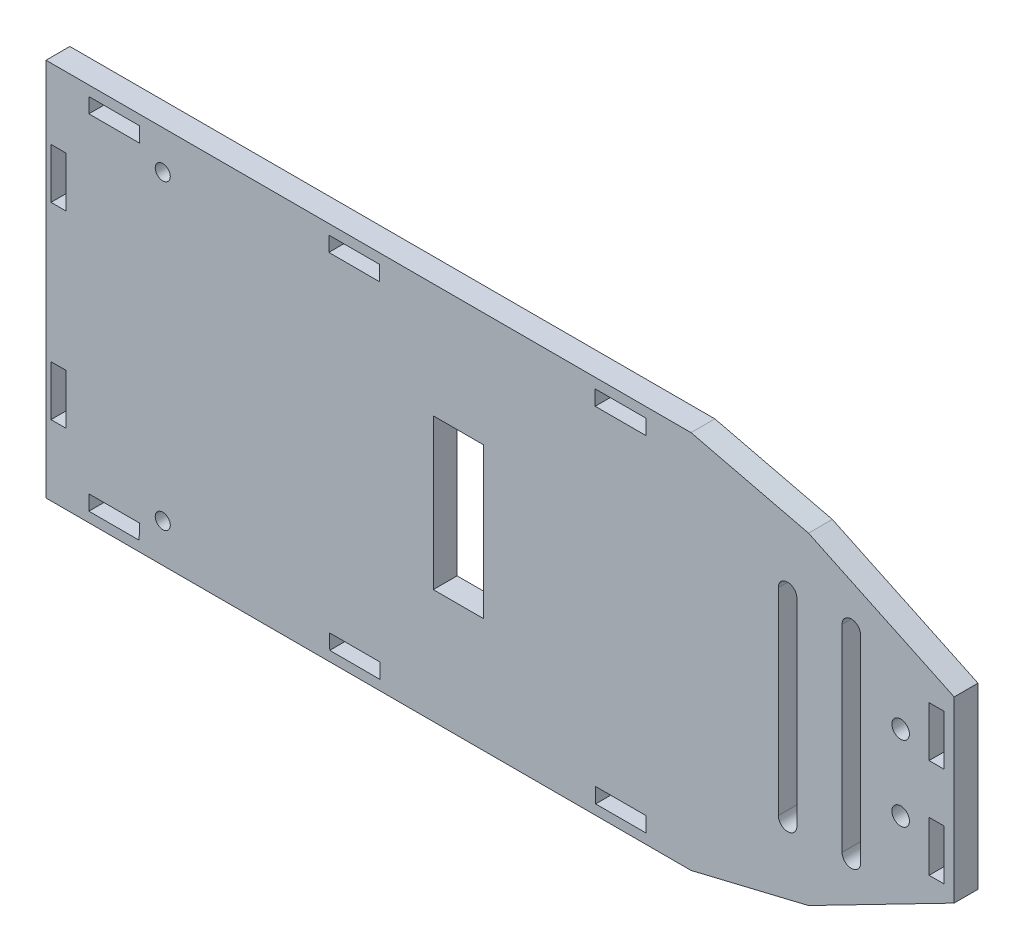
SolidWorks part; units mm, degrees
ref_plane "Front Plane" through (0, 0, 0) normal (0, 0, 1) x (1, 0, 0)
ref_plane "Top Plane" through (0, 0, 0) normal (0, 1, 0) x (1, 0, 0)
ref_plane "Right Plane" through (0, 0, 0) normal (1, 0, 0) x (0, 0, -1)
sketch "Sketch1" plane through (0, 0, 0) normal (0, 0, 1) x (1, 0, 0)
  line L1 (-90.5, -37.785) -> (90.5, -37.785)
  line L2 (-90.5, -37.785) -> (-90.5, 37.785)
  line L3 (-90.5, 37.785) -> (90.5, 37.785)
  line L4 (90.5, -37.785) -> (90.5, 37.785)
  line L5 (-90.5, -37.785) -> (90.5, 37.785) construction
  line L6 (-90.5, 37.785) -> (90.5, -37.785) construction
  point P0 (0, 0)
extrude "Boss-Extrude2" add sketch "Sketch1" along normal blind 4.75
sketch "Sketch6" plane through (0, 0, 4.75) normal (0, 0, 1) x (1, 0, 0)
  line L0 (-90.5, 0) -> (90.5, 0) construction
  line L1 (-90.5, 37.785) -> (-90.5, -37.785) construction
  line L2 (90.5, -37.785) -> (90.5, 37.785) construction
  line L3 (0, 37.785) -> (0, -37.785) construction
  line L4 (90.5, 37.785) -> (-90.5, 37.785) construction
  line L5 (-90.5, -37.785) -> (90.5, -37.785) construction
  line L10 (-17.18, 37.785) -> (-17.18, -37.785) construction
  line L11 (-81.9552, 32.802) -> (-71.8128, 32.7986)
  line L12 (-89.5, 23.75) -> (-86.5, 23.75)
  line L13 (-89.5, 23.75) -> (-89.5, 13.75)
  line L14 (-89.5, 13.75) -> (-86.5, 13.75)
  line L15 (-86.5, 23.75) -> (-86.5, 13.75)
  line L16 (-89.5, -13.75) -> (-86.5, -13.75)
  line L17 (-89.5, -13.75) -> (-89.5, -23.75)
  line L18 (-89.5, -23.75) -> (-86.5, -23.75)
  line L19 (-86.5, -13.75) -> (-86.5, -23.75)
  line L20 (-34.1308, 32.7983) -> (-34.1388, 35.785)
  line L21 (-34.1308, 32.7983) -> (-24.043, 32.7816)
  line L22 (-34.1388, 35.785) -> (-24.043, 35.785)
  line L23 (-24.043, 32.7816) -> (-24.043, 35.785)
  line L24 (-71.8128, 32.7986) -> (-71.8594, 35.785)
  line L25 (-81.9552, 32.802) -> (-81.9552, 35.785)
  line L26 (-81.9552, 35.785) -> (-71.8594, 35.785)
  line L27 (-81.9552, -32.785) -> (-71.8128, -32.7884)
  line L28 (-71.9552, -35.785) -> (-71.8128, -32.7884)
  line L29 (-81.9552, -35.785) -> (-71.9552, -35.785)
  line L30 (-81.9552, -35.785) -> (-81.9552, -32.785)
  line L31 (-33.9472, -35.801) -> (-23.9472, -35.8088)
  line L32 (-33.9472, -35.801) -> (-33.9552, -32.801)
  line L33 (-23.9472, -35.8088) -> (-23.9469, -32.8043)
  line L34 (-33.9552, -32.801) -> (-23.9469, -32.8043)
  line L35 (85.5, 14.9) -> (85.5, 4.9)
  line L36 (88.5, 14.9) -> (88.5, 4.9)
  line L37 (85.5, 4.9) -> (88.5, 4.9)
  line L38 (85.5, 14.9) -> (88.5, 14.9)
  line L39 (88.5, 9.9) -> (85.5, 9.9) construction
  line L40 (29.0528, 32.7816) -> (29.0528, 35.785)
  line L41 (18.957, 32.7816) -> (29.0528, 32.7816)
  line L42 (18.957, 32.7816) -> (18.957, 35.785)
  line L43 (18.957, 35.785) -> (29.0528, 35.785)
  line L44 (19.0531, -32.8054) -> (29.0528, -32.8063)
  line L45 (19.0528, -35.8054) -> (19.0531, -32.8054)
  line L46 (19.0528, -35.8054) -> (29.0528, -35.8063)
  line L47 (29.0528, -35.8063) -> (29.0528, -32.8063)
  line L50 (-67.23, -30.095) -> (79.8334, -30.095) construction
  line L51 (-13.3116, 15) -> (-3.3116, 15)
  line L52 (-13.3116, 15) -> (-13.3116, -15)
  line L53 (-13.3116, -15) -> (-3.3116, -15)
  line L54 (-3.3116, 15) -> (-3.3116, -15)
  line L59 (85.5, -14.9) -> (88.5, -14.9)
  line L64 (85.5, -4.9) -> (85.5, -14.9)
  line L65 (85.5, -4.9) -> (88.5, -4.9)
  line L66 (88.5, -4.9) -> (88.5, -14.9)
  line L67 (38.0552, -37.785) -> (61.4663, -32.14)
  line L68 (61.4663, -32.14) -> (90.5, -17.2)
  line L69 (38.0552, 37.785) -> (61.4663, 32.14)
  line L70 (61.4663, 32.14) -> (90.5, 18.3856)
  line L71 (79.8334, -30.095) -> (79.8334, -36.495)
  circle A2 centre (-67.23, 30.095) radius 1.5
  circle A3 centre (-67.23, -30.095) radius 1.5
  circle A12 centre (70.0065, -12.7534) radius 1.85
  circle A13 centre (70.0065, 12.8925) radius 1.85
  circle A14 centre (70.0065, 0) radius 1.85
  circle A15 centre (57.3065, 12.8925) radius 1.85
  circle A16 centre (57.3065, 0) radius 1.85
  circle A17 centre (57.3065, -12.7534) radius 1.85
  circle A20 centre (79.8334, -7.5) radius 1.75
  circle A21 centre (79.8334, 7.5) radius 1.75
  point P21 (90.5, 0)
  dimension "D1" = 43
  dimension "D3" = 27.5
  dimension "D2" = 43
  dimension "D4" = 15
  dimension "D6" = 2
  dimension "D5" = 7.5
  dimension "D7" = 2
  dimension "D8" = 2
  dimension "D9" = 2
  dimension "D10" = 1
  dimension "D11" = 13.75
  dimension "D12" = 10
extrude "Cut-Extrude7" cut sketch "Sketch6" against normal blind 9
sketch "Sketch9" plane through (0, 0, 4.75) normal (0, 0, 1) x (1, 0, 0)
  line L0 (38.0552, -37.785) -> (38.0552, 37.785)
  line L1 (57.3065, 14.7425) -> (57.3065, 19.7425)
  line L2 (57.3065, -14.6034) -> (57.3065, -19.6034)
  line L3 (70.0065, 14.7425) -> (70.0065, 19.7425)
  line L4 (70.0065, -14.6034) -> (70.0065, -19.6034)
  line L5 (57.3065, -12.7534) -> (59.1565, -12.7534)
  line L6 (57.3065, 19.7425) -> (57.3065, -19.6034) construction
  line L7 (59.1565, 19.7425) -> (59.1565, -19.6034)
  line L8 (55.4565, 19.7425) -> (55.4565, -19.6034)
  line L9 (70.0065, 19.7425) -> (70.0065, -19.6034) construction
  line L10 (71.8565, 19.7425) -> (71.8565, -19.6034)
  line L11 (68.1565, 19.7425) -> (68.1565, -19.6034)
  circle A0 centre (57.3065, 12.8925) radius 1.85 construction
  circle A1 centre (57.3065, -12.7534) radius 1.85 construction
  circle A2 centre (70.0065, 12.8925) radius 1.85 construction
  circle A3 centre (70.0065, -12.7534) radius 1.85 construction
  arc A4 (59.1565, 19.7425) -> (55.4565, 19.7425) centre (57.3065, 19.7425) ccw
  arc A5 (55.4565, -19.6034) -> (59.1565, -19.6034) centre (57.3065, -19.6034) ccw
  arc A6 (71.8565, 19.7425) -> (68.1565, 19.7425) centre (70.0065, 19.7425) ccw
  arc A7 (68.1565, -19.6034) -> (71.8565, -19.6034) centre (70.0065, -19.6034) ccw
  point P26 (57.3065, 0.0695)
  point P31 (70.0065, 0.0695)
  dimension "D1" = 5
extrude "Cut-Extrude8" cut sketch "Sketch9" against normal blind 4.75
